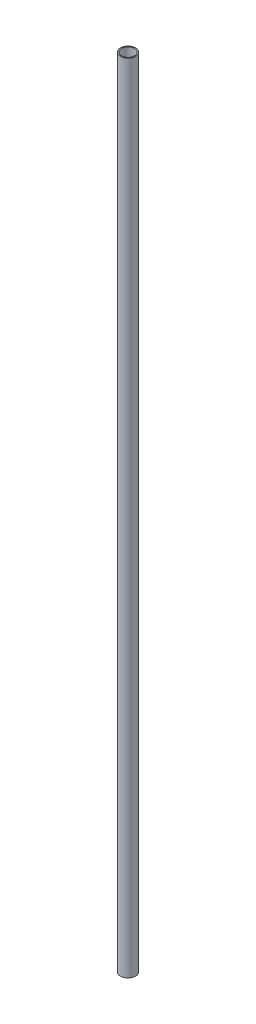
SolidWorks part; units mm, degrees
ref_plane "Front Plane" through (0, 0, 0) normal (0, 0, 1) x (1, 0, 0)
ref_plane "Top Plane" through (0, 0, 0) normal (0, 1, 0) x (1, 0, 0)
ref_plane "Right Plane" through (0, 0, 0) normal (1, 0, 0) x (0, 0, -1)
sketch "Sketch2" plane through (0, 0, 0) normal (0, 1, 0) x (1, 0, 0)
  circle A0 centre (0, 0) radius 13
  circle A1 centre (0, 0) radius 15
  dimension "D1" = 26
  dimension "D2" = 30
extrude "Boss-Extrude1" add sketch "Sketch2" along normal blind 1600
